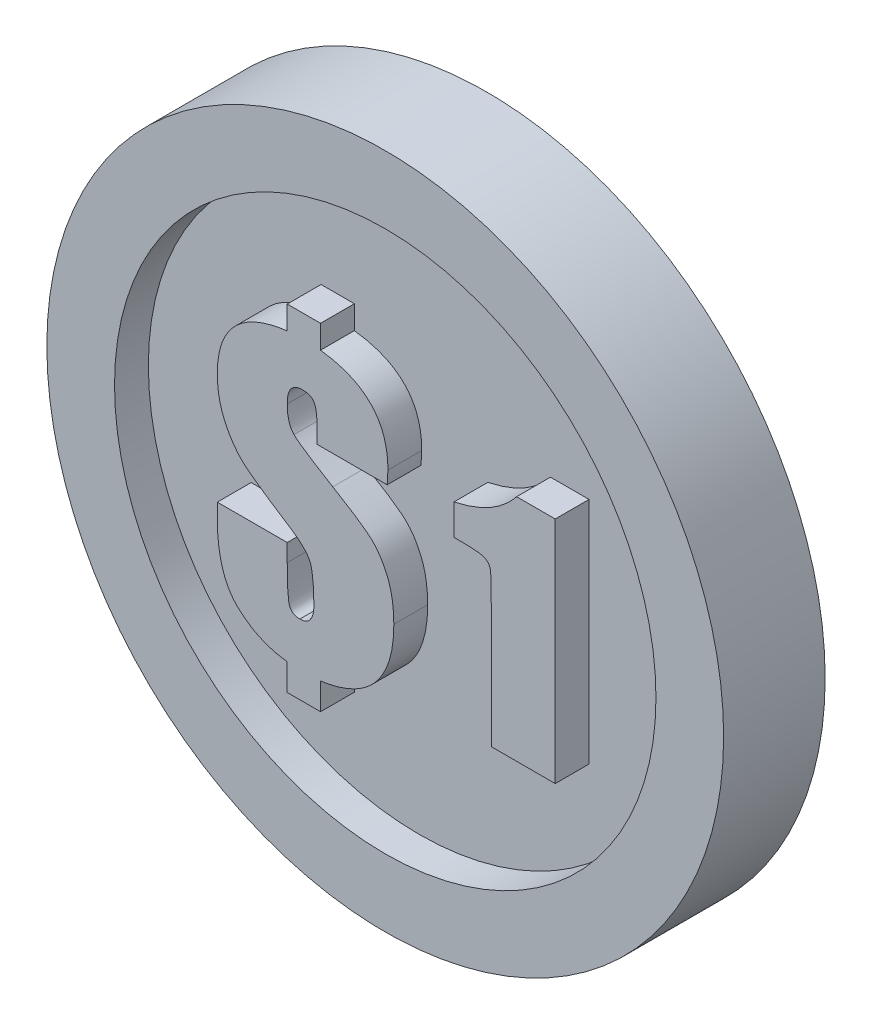
SolidWorks part; units mm, degrees
ref_plane "前视基准面" through (0, 0, 0) normal (0, 0, 1) x (1, 0, 0)
ref_plane "上视基准面" through (0, 0, 0) normal (0, 1, 0) x (1, 0, 0)
ref_plane "右视基准面" through (0, 0, 0) normal (1, 0, 0) x (0, 0, -1)
sketch "草图1" plane through (0, 0, 0) normal (0, 0, 1) x (1, 0, 0)
  circle A0 centre (0, 0) radius 10
  dimension "D1" = 20
extrude "凸台-拉伸1" add sketch "草图1" along normal blind 3
sketch "草图2" plane through (0, 0, 3) normal (0, 0, 1) x (1, 0, 0)
  circle A0 centre (0, 0) radius 10 construction
  circle A1 centre (0, 0) radius 10
  circle A2 centre (0, 0) radius 8
  dimension "D1" = 2
extrude "切除-拉伸1" cut sketch "草图2" against normal blind 1 contours A2
sketch "草图4" plane through (0, 0, 2) normal (0, 0, 1) x (1, 0, 0)
  line L0 (-3.0808, -7.383) -> (3.0808, -7.383) construction
  circle A0 centre (0, 0) radius 8 construction
  arc A1 (-3.0808, -7.383) -> (3.0808, -7.383) centre (0, 0) ccw construction
  text T0 "$" font "Impact" height in points 30
  text T1 "<b>1</b>" font "Impact" height in points 24
  point P4 (0, 0)
  point P6 (-6.4562, -1.8417)
  point P7 (-3.0808, -7.383)
  point P8 (0, 0)
  point P11 (-5.5295, -2.6807)
  point P12 (-5.1537, -2.77)
  point P14 (-1.6497, -2.8197)
  point P15 (-5.2584, -4.5299)
  point P16 (3.0808, -3.4949)
extrude "凸台-拉伸3" add sketch "草图4" along normal blind 1
